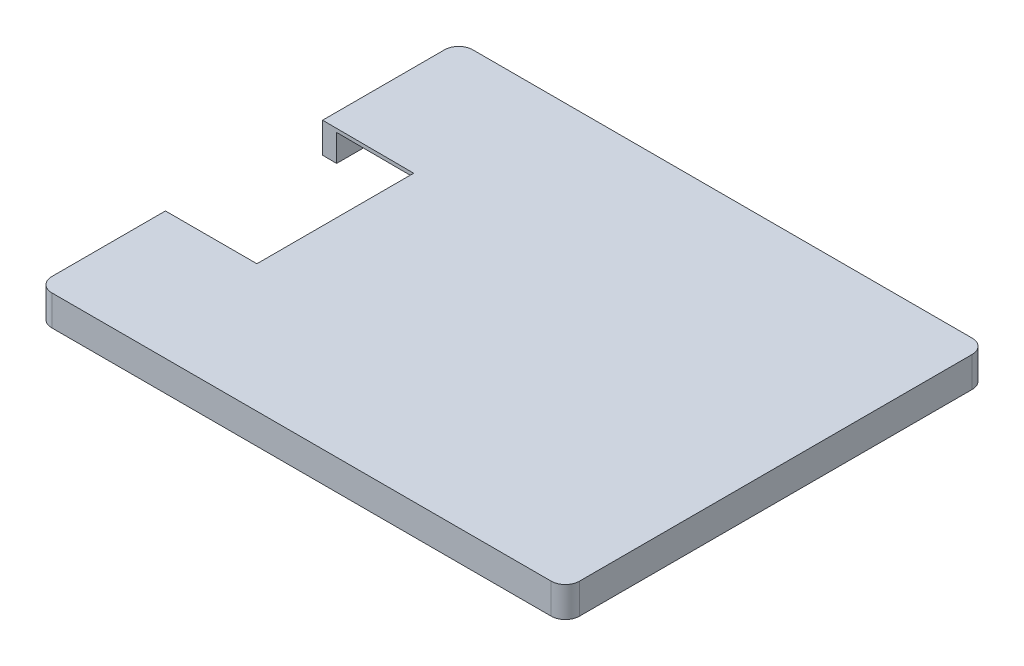
SolidWorks part; units mm, degrees
ref_plane "Front Plane" through (0, 0, 0) normal (0, 0, 1) x (1, 0, 0)
ref_plane "Top Plane" through (0, 0, 0) normal (0, 1, 0) x (1, 0, 0)
ref_plane "Right Plane" through (0, 0, 0) normal (1, 0, 0) x (0, 0, -1)
ref_plane "PREV_HW_TOP" through (0, 15.5, 0) normal (0, 1, 0) x (1, 0, 0)
sketch "Arduino Board Outline" plane through (0, 15.5, 0) normal (0, 1, 0) x (1, 0, 0)
  line L1 (0, 0) -> (68.7, 0)
  line L2 (0, 0) -> (0, 53.6)
  line L3 (0, 53.6) -> (68.7, 53.6)
  line L4 (68.7, 0) -> (68.7, 53.6)
  dimension "D1" = 68.7
  dimension "D2" = 53.6
sketch "Sketch2" plane through (0, 15.5, 0) normal (0, 1, 0) x (1, 0, 0)
  line L4 (69.7, 54.6) -> (-1, 54.6)
  line L5 (-1, 54.6) -> (-1, -1)
  line L6 (-1, -1) -> (69.7, -1)
  line L7 (69.7, -1) -> (69.7, 54.6)
  line L8 (-3, 56.6) -> (-3, -3)
  line L9 (-3, -3) -> (71.7, -3)
  line L10 (71.7, -3) -> (71.7, 56.6)
  line L11 (71.7, 56.6) -> (-3, 56.6)
  line L12 (-3, 56.6) -> (-3, -3)
  line L13 (-3, -3) -> (71.7, -3)
  line L14 (71.7, -3) -> (71.7, 56.6)
  line L15 (71.7, 56.6) -> (-3, 56.6)
  dimension "D1" = 3
  dimension "D2" = 2
extrude "walls" add sketch "Sketch2" along normal blind 3.8
sketch "Sketch3" plane through (71.7, 0, 0) normal (1, 0, 0) x (0, 0, -1)
  line L1 (-3, 19.3) -> (56.6, 19.3)
  line L2 (-3, 19.3) -> (-3, 19.8)
  line L3 (-3, 19.8) -> (56.6, 19.8)
  line L4 (56.6, 19.3) -> (56.6, 19.8)
  point P5 (0, 0)
  dimension "D1" = 0.5
extrude "Boss-Extrude2" add sketch "Sketch3" against normal up to surface (74.7 mm away) up to face at (-3, 17.4, -26.8)
sketch "Sketch4" plane through (0, 15.5, 0) normal (0, 1, 0) x (1, 0, 0)
  line L8 (9.95, 37.2822) -> (-3, 37.335)
  line L9 (-3, 37.335) -> (-3, 15.085)
  line L10 (-3, 15.085) -> (9.95, 15.085)
  line L12 (9.95, 15.085) -> (9.95, 37.2822)
  point P2 (9.95, 37.2822)
  point P4 (0, 0)
  point P6 (9.95, 15.085)
  point P7 (0, 0)
extrude "Cut-Extrude1" cut sketch "Sketch4" along normal up to next
fillet "Fillet1" radius 2 4 edges at (71.7, 17.65, -56.6) (71.7, 17.65, 3) (-3, 17.65, -56.6) (-3, 17.65, 3)
